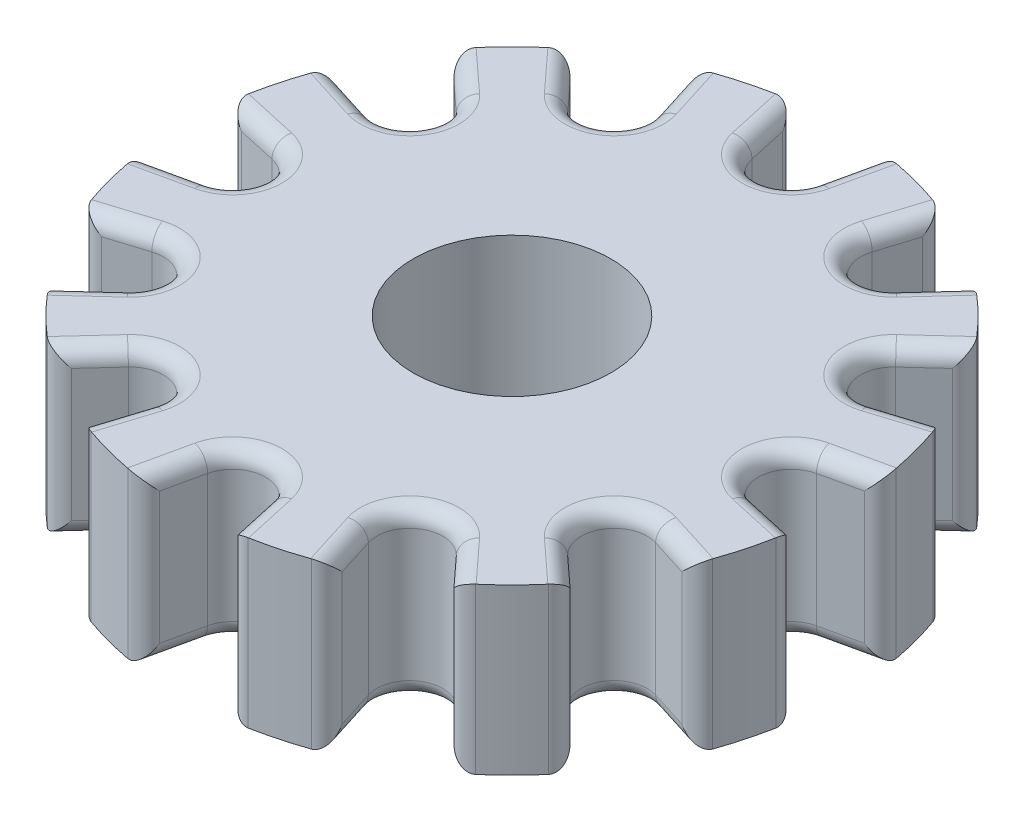
SolidWorks part; units mm, degrees
ref_plane "Front Plane" through (0, 0, 0) normal (0, 0, 1) x (1, 0, 0)
ref_plane "Top Plane" through (0, 0, 0) normal (0, 1, 0) x (1, 0, 0)
ref_plane "Right Plane" through (0, 0, 0) normal (1, 0, 0) x (0, 0, -1)
sketch "Sketch2" plane through (0, 0, 0) normal (0, 1, 0) x (1, 0, 0)
  circle A0 centre (0, 0) radius 20
  dimension "D1" = 40
extrude "Boss-Extrude2" add sketch "Sketch2" along normal mid plane 10
sketch "Sketch3" plane through (0, 5, 0) normal (0, 1, 0) x (1, 0, 0)
  line L1 (1.9525, 16.519) -> (2.685, 19.819)
  line L2 (0, 16.9523) -> (0, 0) construction
  line L4 (-1.9525, 16.519) -> (-2.685, 19.819)
  arc A0 (2.685, 19.819) -> (-2.685, 19.819) centre (0, 0) ccw
  arc A1 (-1.9525, 16.519) -> (1.9525, 16.519) centre (0, 16.9523) ccw
  circle A6 centre (0, 0) radius 20 construction
  dimension "D2" = 4
  dimension "D3" = 25.03
  dimension "D1" = 3.3
sketch "Sketch4" plane through (0, 5, 0) normal (0, 1, 0) x (1, 0, 0)
  circle A0 centre (0, 0) radius 6
  dimension "D1" = 12
extrude "Cut-Extrude3" cut sketch "Sketch4" against normal blind 10
extrude "Cut-Extrude5" cut sketch "Sketch3" against normal blind 10
fillet "Fillet1" radius 1 8 edges at (2.3187, -5, -18.169) (2.3187, 5, -18.169) (0, -5, -14.9523) (0, 5, -14.9523) (-2.685, 0, -19.819) (-2.3187, -5, -18.169) (-2.3187, 5, -18.169) (2.685, 0, -19.819)
pattern_circular "CirPattern3" count 12 over 360 about axis through (0, 0, 0) along (0, 1, 0) of "Cut-Extrude5", "Fillet1"
